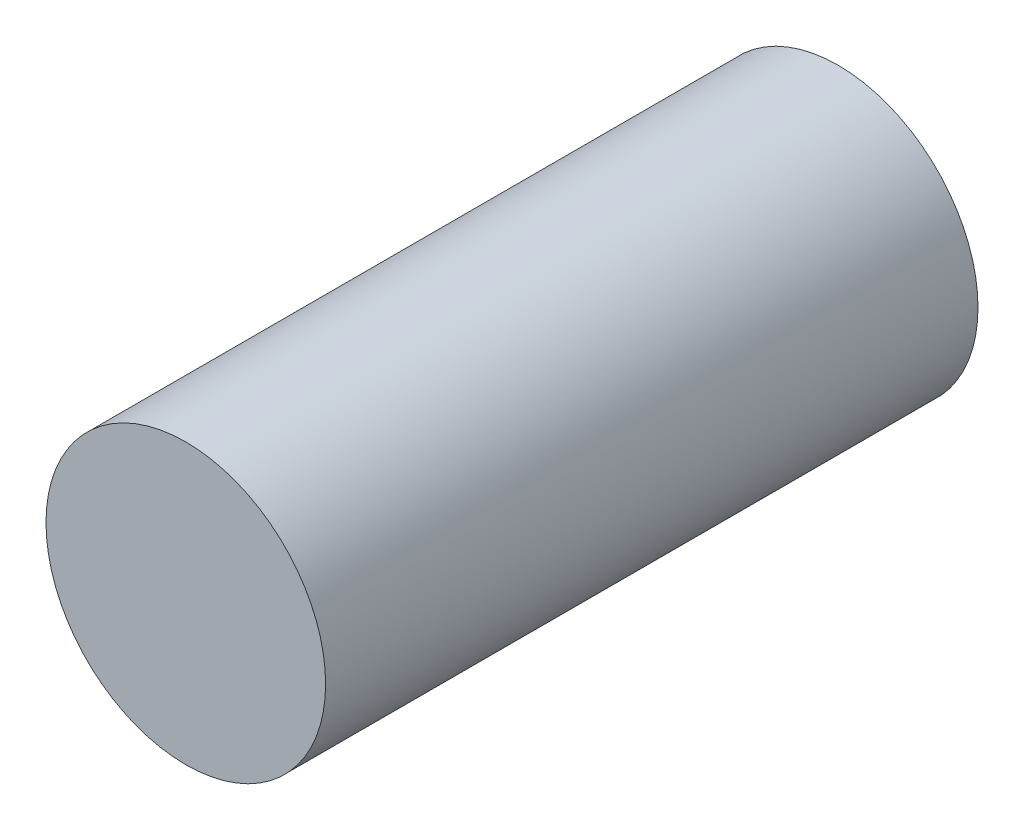
SolidWorks part; units mm, degrees
ref_plane "Front Plane" through (0, 0, 0) normal (0, 0, 1) x (1, 0, 0)
ref_plane "Top Plane" through (0, 0, 0) normal (0, 1, 0) x (1, 0, 0)
ref_plane "Right Plane" through (0, 0, 0) normal (1, 0, 0) x (0, 0, -1)
sketch "Sketch1" plane through (0, 0, 0) normal (0, 0, 1) x (1, 0, 0)
  circle A0 centre (0, 0) radius 7.5
  dimension "D1" = 15
extrude "Boss-Extrude1" add sketch "Sketch1" along normal blind 35
